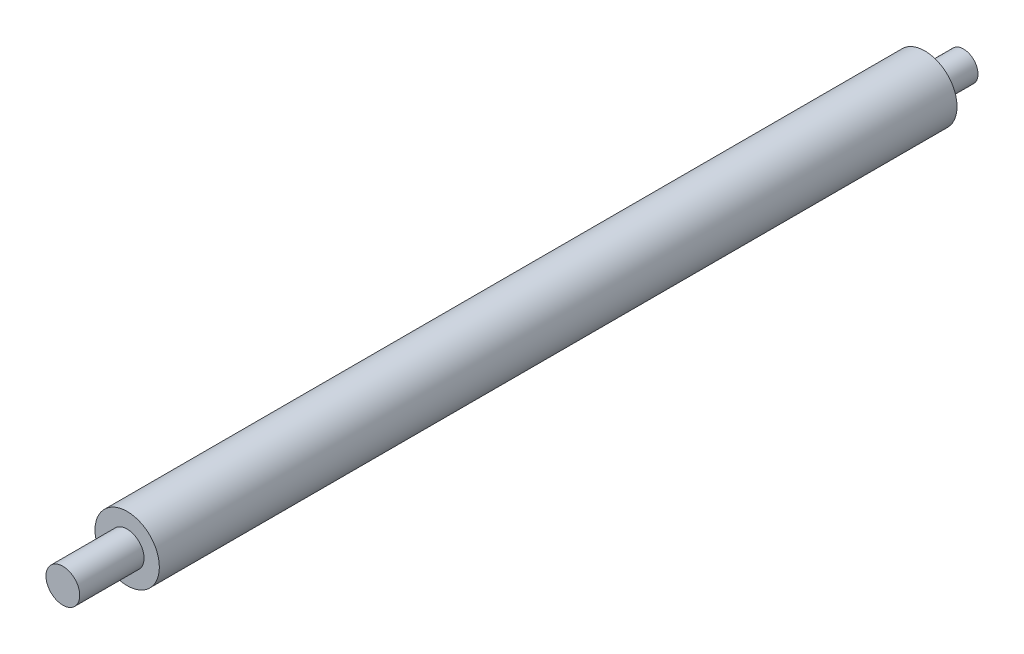
SolidWorks part; units mm, degrees
ref_plane "Front Plane" through (0, 0, 0) normal (0, 0, 1) x (1, 0, 0)
ref_plane "Top Plane" through (0, 0, 0) normal (0, 1, 0) x (1, 0, 0)
ref_plane "Right Plane" through (0, 0, 0) normal (1, 0, 0) x (0, 0, -1)
sketch "Sketch1" plane through (0, 0, 0) normal (0, 0, 1) x (1, 0, 0)
  circle A0 centre (0, 0) radius 25
  dimension "D1" = 50
extrude "Boss-Extrude1" add sketch "Sketch1" along normal blind 700
sketch "Sketch2" plane through (0, 0, 700) normal (0, 0, 1) x (1, 0, 0)
  circle A0 centre (0, 0) radius 13.1192
  circle A1 centre (0, 0) radius 25
extrude "Cut-Extrude1" cut sketch "Sketch2" against normal blind 50
sketch "Sketch3" plane through (0, 0, 0) normal (0, 0, -1) x (-1, 0, 0)
  circle A0 centre (0, 0) radius 11.3204
  circle A1 centre (0, 0) radius 25
extrude "Cut-Extrude2" cut sketch "Sketch3" against normal blind 30
